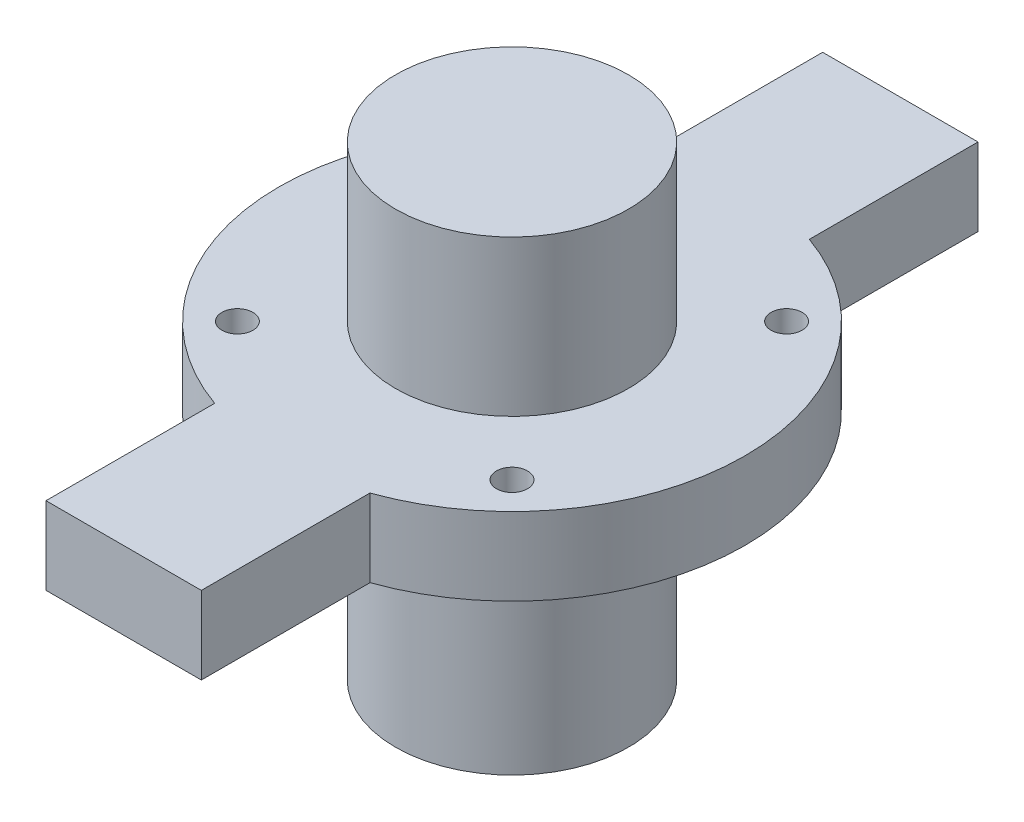
SolidWorks part; units mm, degrees
ref_plane "Front Plane" through (0, 0, 0) normal (0, 0, 1) x (1, 0, 0)
ref_plane "Top Plane" through (0, 0, 0) normal (0, 1, 0) x (1, 0, 0)
ref_plane "Right Plane" through (0, 0, 0) normal (1, 0, 0) x (0, 0, -1)
sketch "Sketch1" plane through (0, 0, 0) normal (0, 1, 0) x (1, 0, 0)
  line L0 (0, 0) -> (0, 20.806) construction
  line L1 (0, 0) -> (-17.6777, 17.6777) construction
  circle A0 centre (0, 0) radius 15
  circle A1 centre (-17.6777, 17.6777) radius 2
  circle A2 centre (17.6777, 17.6777) radius 2
  circle A3 centre (17.6777, -17.6777) radius 2
  circle A4 centre (-17.6777, -17.6777) radius 2
  circle A5 centre (0, 0) radius 30
  point P15 (0, 0)
  dimension "D1" = 30
  dimension "D4" = 4
  dimension "D6" = 60
  dimension "D2" = 25
  dimension "D3" = 45
  dimension "D5" = 4
extrude "Boss-Extrude1" add sketch "Sketch1" along normal blind 10
sketch "Sketch2" plane through (0, 10, 0) normal (0, 1, 0) x (1, 0, 0)
  line L0 (10, 11.1803) -> (10, 50)
  line L1 (-10, -50) -> (10, -50)
  line L2 (-10, -50) -> (-10, 50)
  line L3 (-10, 50) -> (10, 50)
  line L4 (10, -50) -> (10, -11.1803)
  line L5 (-10, -50) -> (-2.9417, -14.7087) construction
  line L6 (-10, 50) -> (-2.9417, 14.7087) construction
  line L7 (2.9417, 14.7087) -> (10, 50) construction
  line L8 (2.9417, -14.7087) -> (10, -50) construction
  arc A0 (-10, -11.1803) -> (10, -11.1803) centre (0, 0) ccw
  arc A1 (10, 11.1803) -> (-10, 11.1803) centre (0, 0) ccw
  point P0 (0, 0)
  circle M7 centre (0, 0) radius 30
  circle M8 centre (0, 0) radius 15
  dimension "D1" = 100
  dimension "D2" = 20
extrude "Boss-Extrude2" add sketch "Sketch2" against normal blind 10 contours L2 L0 M8 M7 | L3 L2 L0 M7 | L4 L2 M7 M8 | L1 L4 L2 M7
sketch "Sketch5" plane through (0, 0, 0) normal (0, 1, 0) x (1, 0, 0)
  circle A0 centre (0, 0) radius 15
extrude "Boss-Extrude3" add sketch "Sketch5" along normal mid plane 60
